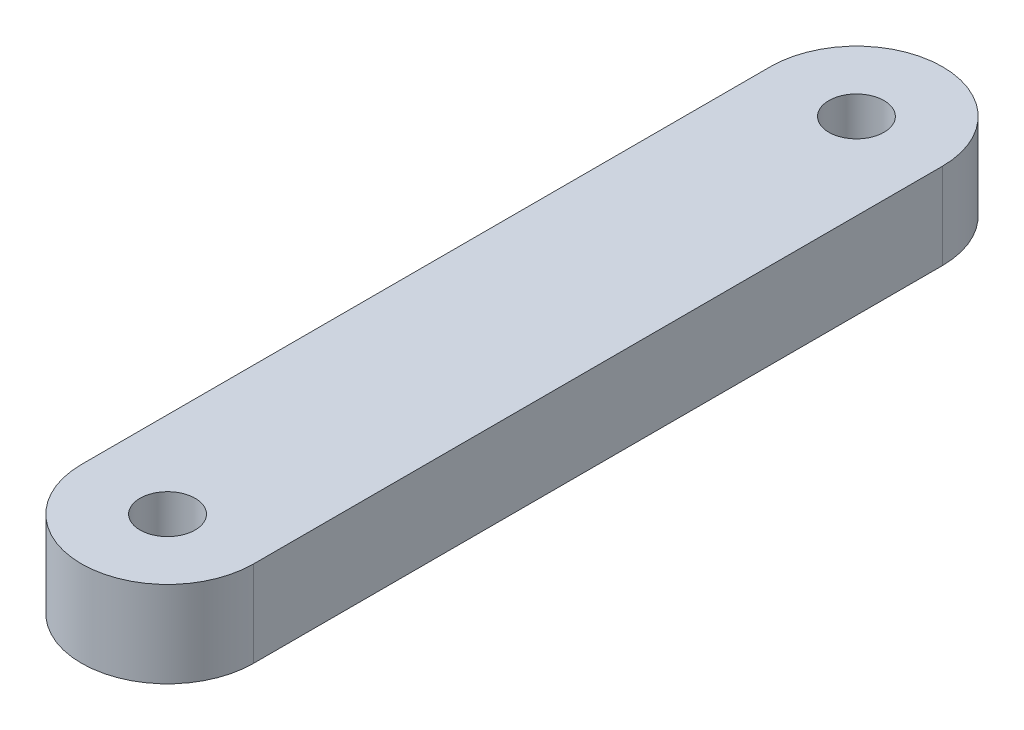
SolidWorks part; units mm, degrees
ref_plane "Front Plane" through (0, 0, 0) normal (0, 0, 1) x (1, 0, 0)
ref_plane "Top Plane" through (0, 0, 0) normal (0, 1, 0) x (1, 0, 0)
ref_plane "Right Plane" through (0, 0, 0) normal (1, 0, 0) x (0, 0, -1)
sketch "Sketch1" plane through (0, 0, 0) normal (0, 1, 0) x (1, 0, 0)
  line L0 (0, 0) -> (0, 40) construction
  line L1 (-5, 0) -> (-5, 40)
  line L2 (5, 0) -> (5, 40)
  arc A0 (-5, 0) -> (5, 0) centre (0, 0) ccw
  arc A1 (5, 40) -> (-5, 40) centre (0, 40) ccw
  circle A2 centre (0, 40) radius 1.6
  circle A3 centre (0, 0) radius 1.6
  point P3 (0, 20)
  dimension "D3" = 3.2
  dimension "D1" = 10
  dimension "D2" = 40
extrude "Boss-Extrude1" add sketch "Sketch1" along normal blind 5
